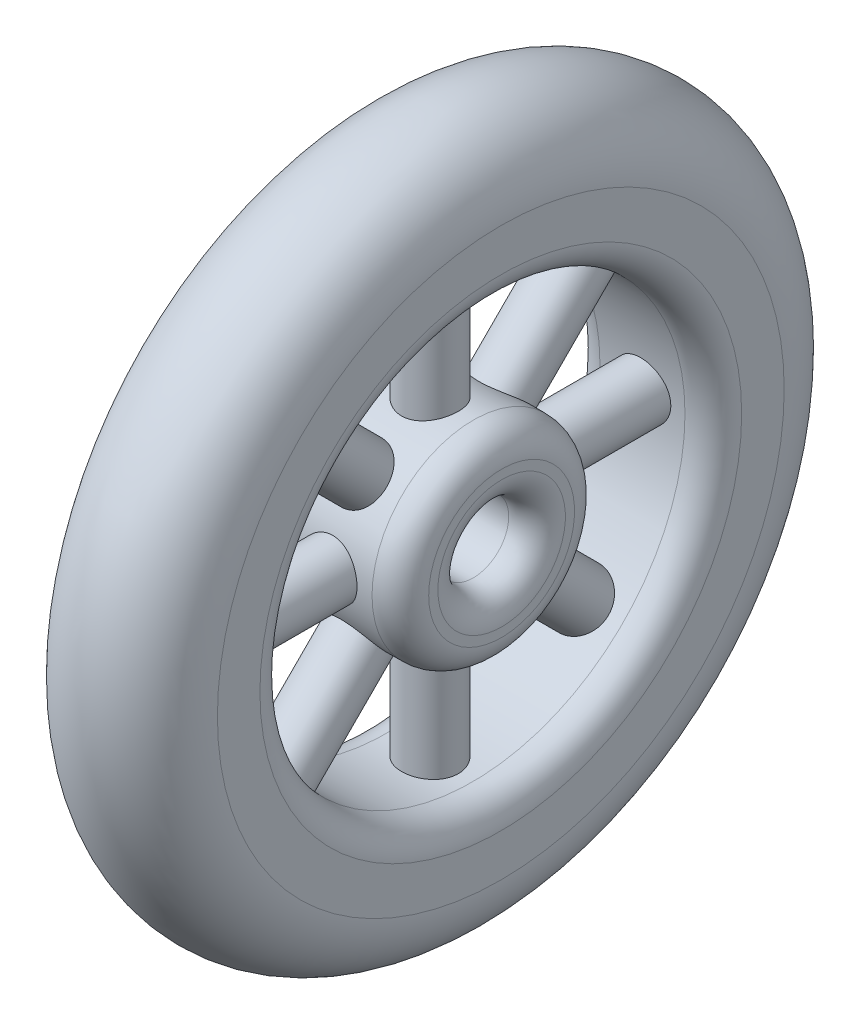
SolidWorks part; units mm, degrees
material "ABS"
ref_plane "Front Plane" through (0, 0, 0) normal (0, 0, 1) x (1, 0, 0)
ref_plane "Top Plane" through (0, 0, 0) normal (0, 1, 0) x (1, 0, 0)
ref_plane "Right Plane" through (0, 0, 0) normal (1, 0, 0) x (0, 0, -1)
sketch "Sketch3" plane through (0, 0, 0) normal (0, 0, 1) x (1, 0, 0)
  line L2 (13.3734, 0) -> (-13.3734, 0) construction
  line L4 (0, 1.5875) -> (0, 15.875) construction
  line L5 (-1.9422, 1.5875) -> (1.9422, 1.5875)
  line L6 (1.9422, 4.5382) -> (-1.9422, 4.5382)
  line L7 (0, -8.7312) -> (0, 8.7312) construction
  line L8 (-11.9772, 0) -> (12.3381, 0) construction
  line L11 (3.2122, 2.8575) -> (3.2122, 3.2682)
  line L13 (-3.2122, 2.8575) -> (-3.2122, 3.2682)
  line L14 (-3.175, 12.7) -> (-3.175, 10.795)
  line L15 (-1.905, 9.525) -> (1.905, 9.525)
  line L16 (3.175, 10.795) -> (3.175, 12.7)
  arc A0 (3.175, 12.7) -> (-3.175, 12.7) centre (0, 12.7) ccw
  arc A1 (1.905, 9.525) -> (3.175, 10.795) centre (1.905, 10.795) ccw
  arc A2 (-1.905, 9.525) -> (-3.175, 10.795) centre (-1.905, 10.795) cw
  arc A3 (-3.2122, 2.8575) -> (-1.9422, 1.5875) centre (-1.9422, 2.8575) ccw
  arc A4 (-3.2122, 3.2682) -> (-1.9422, 4.5382) centre (-1.9422, 3.2682) cw
  arc A5 (3.2122, 2.8575) -> (1.9422, 1.5875) centre (1.9422, 2.8575) cw
  arc A6 (3.2122, 3.2682) -> (1.9422, 4.5382) centre (1.9422, 3.2682) ccw
  dimension "D1" = 6.35
  dimension "D2" = 1.27
  dimension "D3" = 1.27
  dimension "D4" = 3.2122
  dimension "D5" = 1.5875
  dimension "D6" = 4.5382
  dimension "D7" = 15.875
revolve "Revolve1" add sketch "Sketch3" angle 360 about L8
sketch "Sketch5" plane through (0, 0, 0) normal (1, 0, 0) x (0, 0, -1)
  line L0 (0, 3.0628) -> (0, 12.7)
  line L1 (0, 2.8575) -> (0, 3.2682) construction
sweep "Sweep1" add path "Sketch5" circular profile diameter 2.54 parameters "D3"=2.54
pattern_circular "CirPattern1" count 8 over 360 about axis through (-11.9772, 0, 0) along (1, 0, 0) of "Sweep1"
scale "Scale2" scale about centroid uniform scaling yes scale factor 1.15
